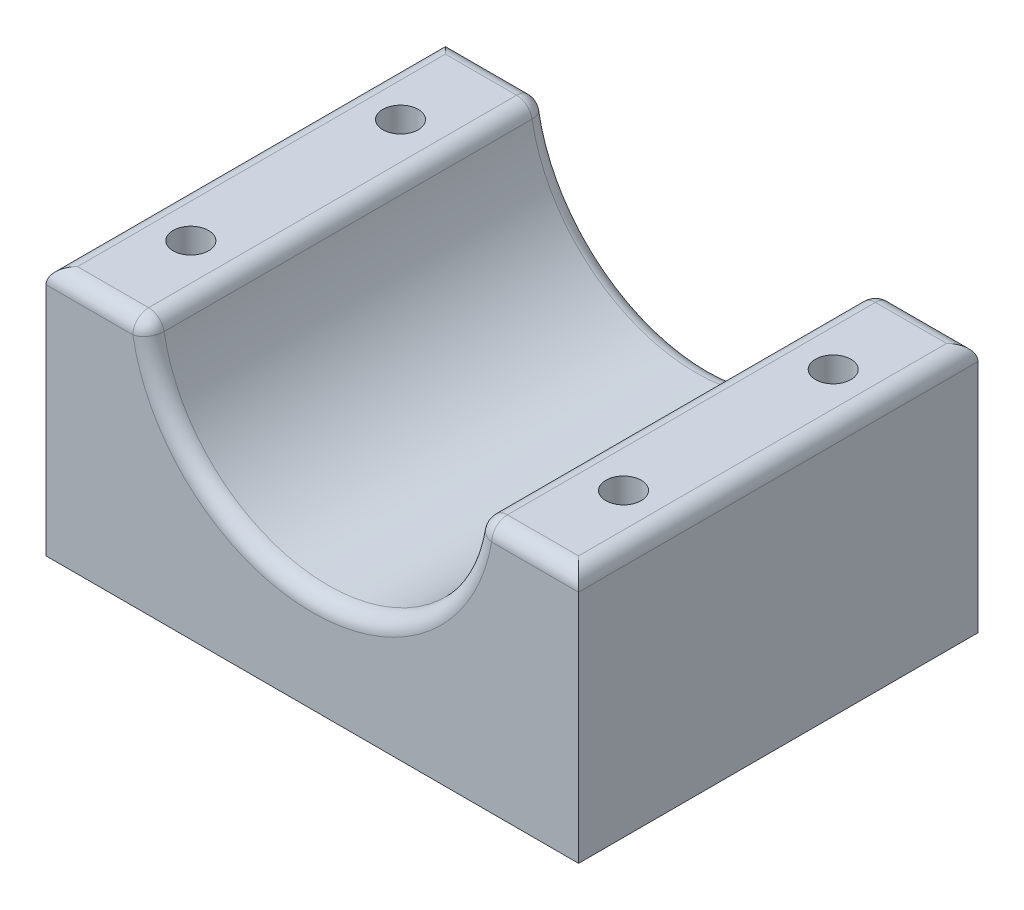
SolidWorks part; units mm, degrees
material "Malleable Cast Iron"
ref_plane "Front Plane" through (0, 0, 0) normal (0, 0, 1) x (1, 0, 0)
ref_plane "Top Plane" through (0, 0, 0) normal (0, 1, 0) x (1, 0, 0)
ref_plane "Right Plane" through (0, 0, 0) normal (1, 0, 0) x (0, 0, -1)
sketch "Sketch1" plane through (0, 0, 0) normal (0, 0, 1) x (1, 0, 0)
  line L1 (-50.8, -23.9) -> (50.8, -23.9)
  line L2 (-50.8, -23.9) -> (-50.8, 23.9)
  line L3 (-50.8, 23.9) -> (50.8, 23.9)
  line L4 (50.8, -23.9) -> (50.8, 23.9)
  line L5 (-50.8, -23.9) -> (50.8, 23.9) construction
  line L6 (-50.8, 23.9) -> (50.8, -23.9) construction
  point P0 (0, 0)
  dimension "D1" = 47.8
  dimension "D2" = 101.6
extrude "Boss-Extrude1" add sketch "Sketch1" along normal blind 76.2
sketch "Sketch2" plane through (0, 0, 76.2) normal (0, 0, 1) x (1, 0, 0)
  line L0 (-50.8, -23.9) -> (50.8, -23.9) construction
  circle A0 centre (0, 26.9) radius 31.75
  dimension "D1" = 63.5
  dimension "D2" = 50.8
extrude "Cut-Extrude1" cut sketch "Sketch2" against normal through all
fillet "Fillet1" radius 3 10 edges at (50.8, 23.9, 38.1) (41.204, 23.9, 76.2) (41.204, 23.9, 0) (-31.6079, 23.9, 38.1) (31.6079, 23.9, 38.1) (0, -4.85, 76.2) (0, -4.85, 0) (-50.8, 23.9, 38.1) (-41.204, 23.9, 0) (-41.204, 23.9, 76.2)
hole_wizard "CBORE for 1/4 Binding Head Machine Screw1" positions "Sketch3" profile "Sketch4" counterbore size "1/4" standard "ANSI Inch" end condition through all
sketch "Sketch3" plane through (0, -23.9, 0) normal (0, -1, 0) x (-1, 0, 0)
  line L0 (50.8, -76.2) -> (-50.8, -76.2) construction
  line L1 (50.8, -76.2) -> (50.8, 0) construction
  point P0 (41.27, -58.1)
  dimension "D1" = 18.1
  dimension "D2" = 9.53
sketch "Sketch4" plane through (-41.27, -23.9, 58.1) normal (1, 0, 0) x (0, 0, -1)
  line L0 (0, 0) -> (0, 47.8)
  line L1 (0, 47.8) -> (3.3782, 47.8)
  line L3 (3.3782, 47.8) -> (3.3782, 4.191)
  line L4 (7.1437, 4.191) -> (3.3782, 4.191)
  line L5 (7.1437, 4.191) -> (7.1437, 0.5328)
  line L6 (7.1437, 0.5328) -> (7.7788, 0)
  line L7 (7.7788, 0) -> (0, 0)
  line L8 (-7.1437, 0.5328) -> (-7.7788, 0) construction
  line L11 (0, -6.35) -> (0, 107.95) construction
  dimension "Thru Hole Dia." = 6.7564
  dimension "Thru Hole Depth" = 47.8
  dimension "C'Bore Dia." = 14.2875
  dimension "C'Bore Depth" = 4.191
  dimension "Near C'Sink Dia." = 15.5575
  dimension "Near C'Sink Angle" = 100
pattern_linear "LPattern1" count 2 spacing 82.55 along (1, 0, 0) count 2 spacing 40 along (0, 0, -1) of "CBORE for 1/4 Binding Head Machine Screw1"
